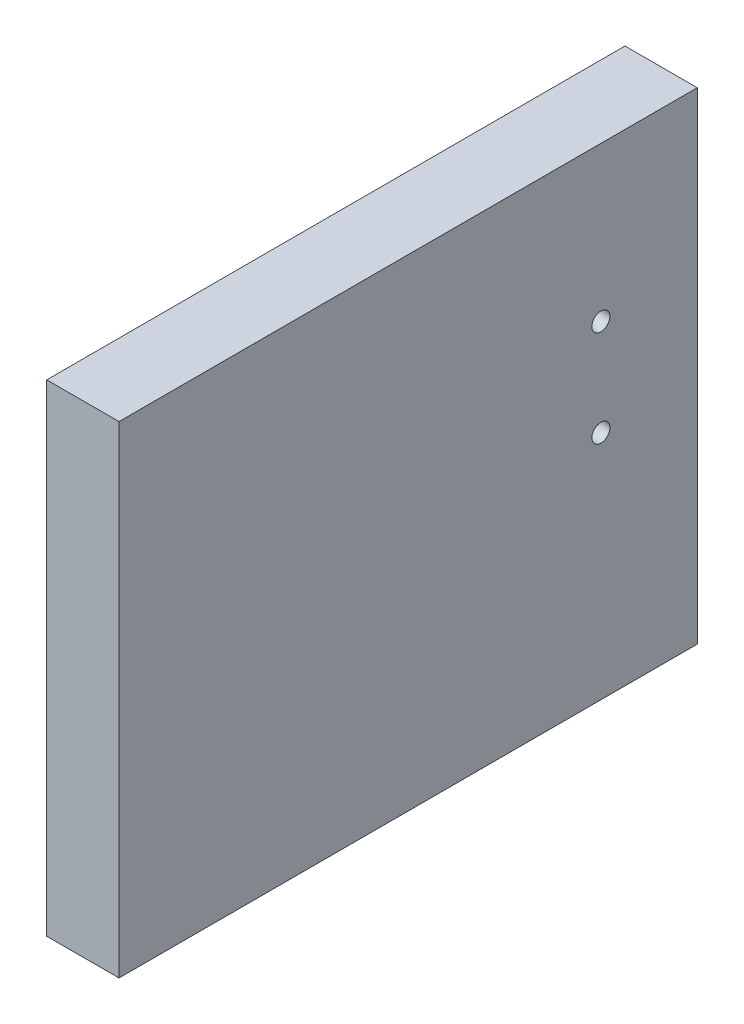
SolidWorks part; units mm, degrees
ref_plane "Front Plane" through (0, 0, 0) normal (0, 0, 1) x (1, 0, 0)
ref_plane "Top Plane" through (0, 0, 0) normal (0, 1, 0) x (1, 0, 0)
ref_plane "Right Plane" through (0, 0, 0) normal (1, 0, 0) x (0, 0, -1)
sketch "Sketch1" plane through (0, 0, 0) normal (0, 0, 1) x (1, 0, 0)
  line L1 (-9.525, 63.5) -> (9.525, 63.5)
  line L2 (-9.525, 63.5) -> (-9.525, -63.5)
  line L3 (-9.525, -63.5) -> (9.525, -63.5)
  line L4 (9.525, 63.5) -> (9.525, -63.5)
  line L5 (-9.525, 63.5) -> (9.525, -63.5) construction
  line L6 (-9.525, -63.5) -> (9.525, 63.5) construction
  point P0 (0, 0)
  dimension "D1" = 127
  dimension "D2" = 19.05
extrude "Boss-Extrude1" add sketch "Sketch1" along normal blind 152.4
sketch "Sketch2" plane through (9.525, 0, 0) normal (1, 0, 0) x (0, 0, -1)
  circle A0 centre (-25.4, 22.86) radius 2.3813
  circle A1 centre (-25.4, -2.54) radius 2.3812
extrude "Cut-Extrude1" cut sketch "Sketch2" against normal through all
